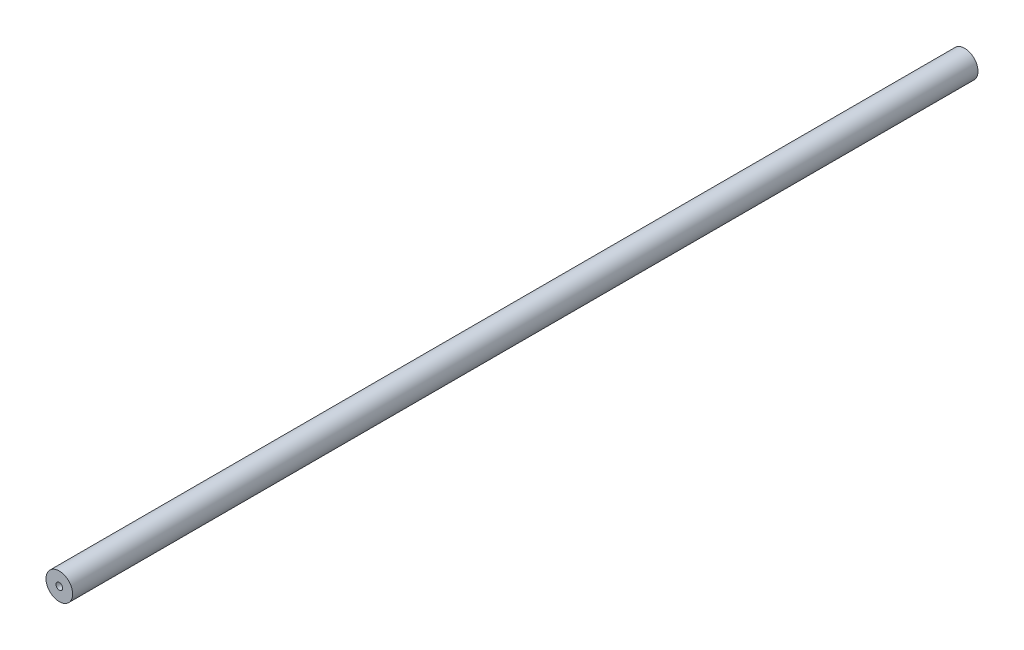
SolidWorks part; units mm, degrees
ref_plane "Front Plane" through (0, 0, 0) normal (0, 0, 1) x (1, 0, 0)
ref_plane "Top Plane" through (0, 0, 0) normal (0, 1, 0) x (1, 0, 0)
ref_plane "Right Plane" through (0, 0, 0) normal (1, 0, 0) x (0, 0, -1)
sketch "Sketch1" plane through (0, 0, 0) normal (0, 0, 1) x (1, 0, 0)
  circle A0 centre (0, 0) radius 12.7
extrude "Boss-Extrude1" add sketch "Sketch1" along normal blind 863.6
sketch "Sketch2" plane through (0, 0, 863.6) normal (0, 0, 1) x (1, 0, 0)
  circle A0 centre (0, 0) radius 3.175
extrude "Cut-Extrude1" cut sketch "Sketch2" against normal blind 863.6
